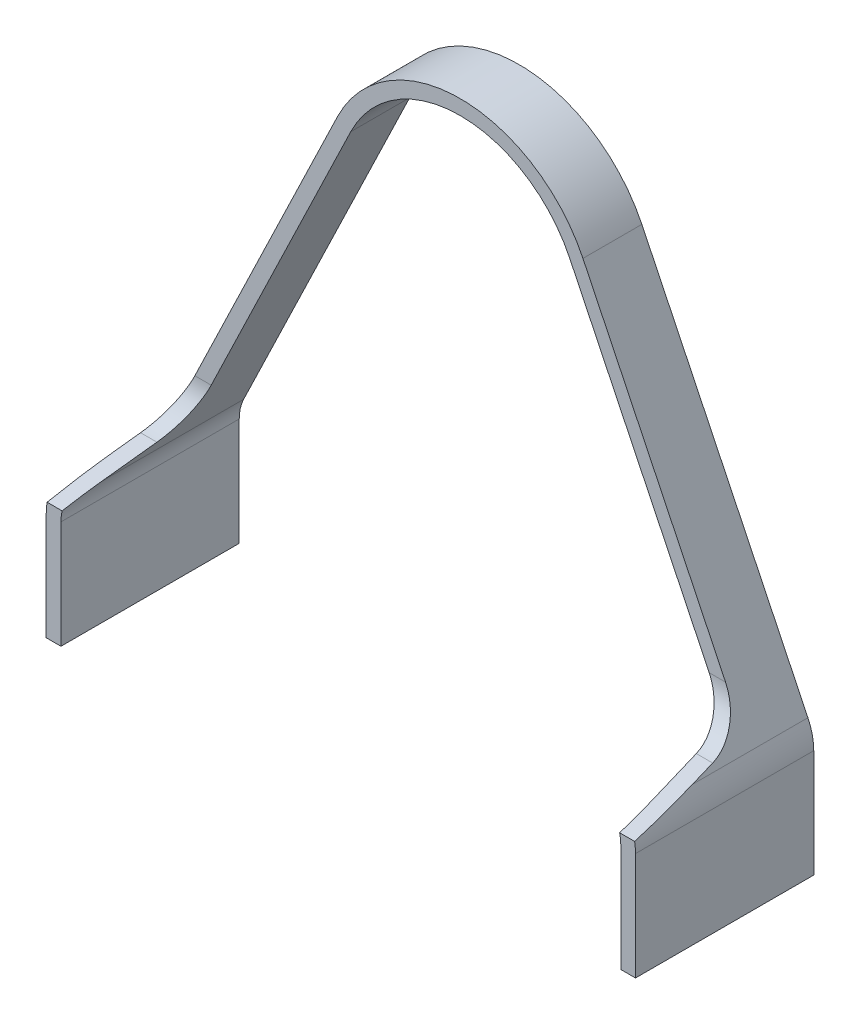
SolidWorks part; units mm, degrees
ref_plane "前视基准面" through (0, 0, 0) normal (0, 0, 1) x (1, 0, 0)
ref_plane "上视基准面" through (0, 0, 0) normal (0, 1, 0) x (1, 0, 0)
ref_plane "右视基准面" through (0, 0, 0) normal (1, 0, 0) x (0, 0, -1)
sketch "草图1" plane through (0, 0, 0) normal (0, 0, 1) x (1, 0, 0)
  line L0 (-190, -210.8575) -> (-190, -284)
  line L1 (-190, -284) -> (-200, -284)
  line L2 (-200, -284) -> (-200, -210.8575)
  line L3 (0, 0) -> (0, -391.576) construction
  line L4 (200, -284) -> (200, -210.8575)
  line L5 (190, -284) -> (200, -284)
  line L6 (190, -210.8575) -> (190, -284)
  line L7 (-83.3137, 40.188) -> (-196.0275, -193.4789)
  line L8 (-74.3068, 35.8434) -> (-187.0207, -197.8235)
  line L9 (74.3068, 35.8434) -> (187.0207, -197.8235)
  line L10 (83.3137, 40.188) -> (196.0275, -193.4789)
  arc A0 (83.3137, 40.188) -> (-83.3137, 40.188) centre (0, 0) ccw
  arc A1 (74.3068, 35.8434) -> (-74.3068, 35.8434) centre (0, 0) ccw
  arc A2 (190, -210.8575) -> (187.0207, -197.8235) centre (160, -210.8575) ccw
  arc A3 (-190, -210.8575) -> (-187.0207, -197.8235) centre (-160, -210.8575) cw
  arc A4 (200, -210.8575) -> (196.0275, -193.4789) centre (160, -210.8575) ccw
  arc A5 (-200, -210.8575) -> (-196.0275, -193.4789) centre (-160, -210.8575) cw
  point P15 (-190, -204)
  point P18 (190, -204)
  point P21 (-190, -204)
  point P24 (200, -201.7142)
  point P27 (-200, -201.7142)
  dimension "D1" = 185
  dimension "D2" = 165
  dimension "D6" = 30
  dimension "D7" = 40
  dimension "D3" = 400
  dimension "D4" = 10
  dimension "D5" = 284
  dimension "D8" = 80
extrude "凸台-拉伸1" add sketch "草图1" along normal blind 121
sketch "草图2" plane through (-200, 0, 0) normal (-1, 0, 0) x (0, 0, 1)
  line L0 (40, 92.5) -> (40, -160.5064)
  line L1 (62.8086, -189.6317) -> (121, -204)
  line L2 (121, -210.8575) -> (121, -284) construction
  line L3 (121, -204) -> (121, 92.5)
  line L4 (121, 92.5) -> (40, 92.5)
  line L5 (121, 92.5) -> (0, 92.5) construction
  line L6 (0, 92.5) -> (0, 40.188) construction
  line L7 (121, -284) -> (0, -284) construction
  arc A0 (40, -160.5064) -> (62.8086, -189.6317) centre (70, -160.5064) ccw
  point P17 (40, -184)
  dimension "D4" = 30
  dimension "D1" = 40
  dimension "D2" = 80
  dimension "D3" = 276.5
extrude "切除-拉伸1" cut sketch "草图2" against normal through all
